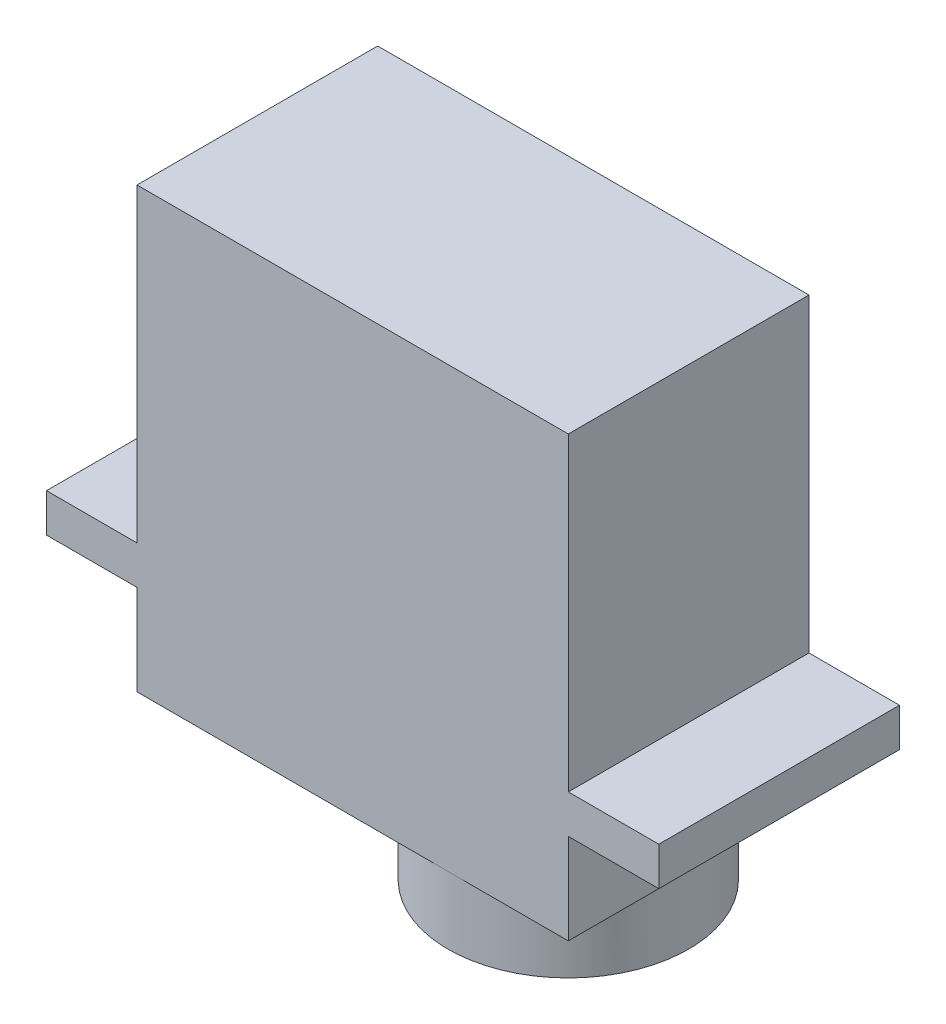
SolidWorks part; units mm, degrees
ref_plane "Front Plane" through (0, 0, 0) normal (0, 0, 1) x (1, 0, 0)
ref_plane "Top Plane" through (0, 0, 0) normal (0, 1, 0) x (1, 0, 0)
ref_plane "Right Plane" through (0, 0, 0) normal (1, 0, 0) x (0, 0, -1)
sketch "Sketch1" plane through (0, 0, 0) normal (0, 1, 0) x (1, 0, 0)
  line L1 (-11.2, 6.25) -> (11.2, 6.25)
  line L2 (-11.2, 6.25) -> (-11.2, -6.25)
  line L3 (-11.2, -6.25) -> (11.2, -6.25)
  line L4 (11.2, 6.25) -> (11.2, -6.25)
  line L5 (-11.2, 6.25) -> (11.2, -6.25) construction
  line L6 (-11.2, -6.25) -> (11.2, 6.25) construction
  point P0 (0, 0)
  dimension "D1" = 22.4
  dimension "D2" = 12.5
extrude "Boss-Extrude1" add sketch "Sketch1" along normal blind 22.8
sketch "Sketch2" plane through (11.2, 0, 0) normal (1, 0, 0) x (0, 0, -1)
  line L0 (-6.25, 4.7) -> (6.25, 4.7)
  line L1 (-6.25, 22.8) -> (-6.25, 0) construction
  line L2 (6.25, 22.8) -> (6.25, 0) construction
  line L3 (-6.25, 6.7) -> (6.25, 6.7)
  line L4 (6.25, 6.7) -> (6.25, 4.7)
  line L5 (-6.25, 6.7) -> (-6.25, 4.7)
  line L6 (-6.25, 22.8) -> (6.25, 22.8) construction
  dimension "D1" = 2
  dimension "D2" = 16.1
extrude "Boss-Extrude2" add sketch "Sketch2" along normal blind 4.7
sketch "Sketch3" plane through (-11.2, 0, 0) normal (-1, 0, 0) x (0, 0, 1)
  line L0 (-6.25, 6.7) -> (6.25, 6.7)
  line L1 (-6.25, 22.8) -> (-6.25, 0) construction
  line L2 (6.25, 22.8) -> (6.25, 0) construction
  line L3 (-6.25, 4.7) -> (6.25, 4.7)
  line L4 (-6.25, 6.7) -> (-6.25, 4.7)
  line L5 (6.25, 6.7) -> (6.25, 4.7)
  line L6 (-6.25, 22.8) -> (6.25, 22.8) construction
  dimension "D1" = 16.1
  dimension "D2" = 2
extrude "Boss-Extrude3" add sketch "Sketch3" along normal blind 4.7
sketch "Sketch4" plane through (0, 0, 0) normal (0, -1, 0) x (1, 0, 0)
  line L0 (-11.2, 0) -> (11.2, 0) construction
  line L1 (-11.2, -6.25) -> (-11.2, 6.25) construction
  line L2 (11.2, 6.25) -> (11.2, -6.25) construction
  line L3 (4.95, -6.25) -> (4.95, 6.25) construction
  line L4 (11.2, -6.25) -> (-11.2, -6.25) construction
  line L5 (-11.2, 6.25) -> (11.2, 6.25) construction
  arc A0 (-0.8421, -2.3482) -> (-0.8421, 2.3482) centre (4.95, 0) ccw
  arc A1 (-0.8421, 2.3482) -> (-0.8421, -2.3482) centre (-1.7, 0) ccw
  dimension "D2" = 5
  dimension "D1" = 6.25
  dimension "D3" = 9.5
extrude "Boss-Extrude5" add sketch "Sketch4" along normal blind 3.5
sketch "Sketch5" plane through (0, -3.5, 0) normal (0, -1, 0) x (1, 0, 0)
  circle A0 centre (4.95, 0) radius 2.5
  dimension "D1" = 5
extrude "Cut-Extrude1" cut sketch "Sketch5" against normal blind 5
